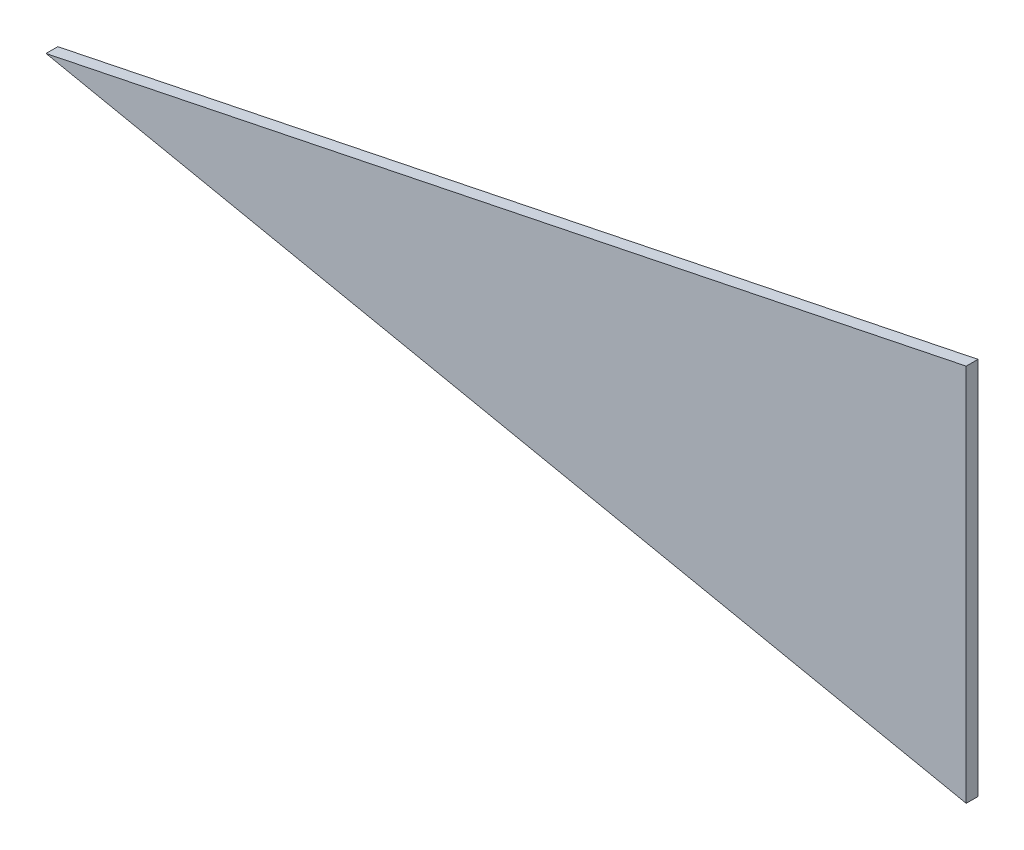
SolidWorks part; units mm, degrees
ref_plane "Front Plane" through (0, 0, 0) normal (0, 0, 1) x (1, 0, 0)
ref_plane "Top Plane" through (0, 0, 0) normal (0, 1, 0) x (1, 0, 0)
ref_plane "Right Plane" through (0, 0, 0) normal (1, 0, 0) x (0, 0, -1)
sketch "Sketch1" plane through (0, 0, 0) normal (0, 0, 1) x (1, 0, 0)
  line L0 (633.3216, 176.6732) -> (633.3216, -353.3268) construction
  line L1 (-654.7001, -88.3268) -> (633.3216, 176.6732) construction
  line L2 (-654.7001, -88.3268) -> (633.3216, -353.3268) construction
  line L3 (613.3216, 152.1394) -> (613.3216, -328.7931)
  line L4 (-555.4548, -88.3268) -> (613.3216, -328.7931)
  line L5 (-555.4548, -88.3268) -> (613.3216, 152.1394)
  dimension "D1" = 1315
  dimension "D2" = 1315
  dimension "D3" = 530
  dimension "D4" = 20
extrude "Boss-Extrude1" add sketch "Sketch1" along normal blind 15
